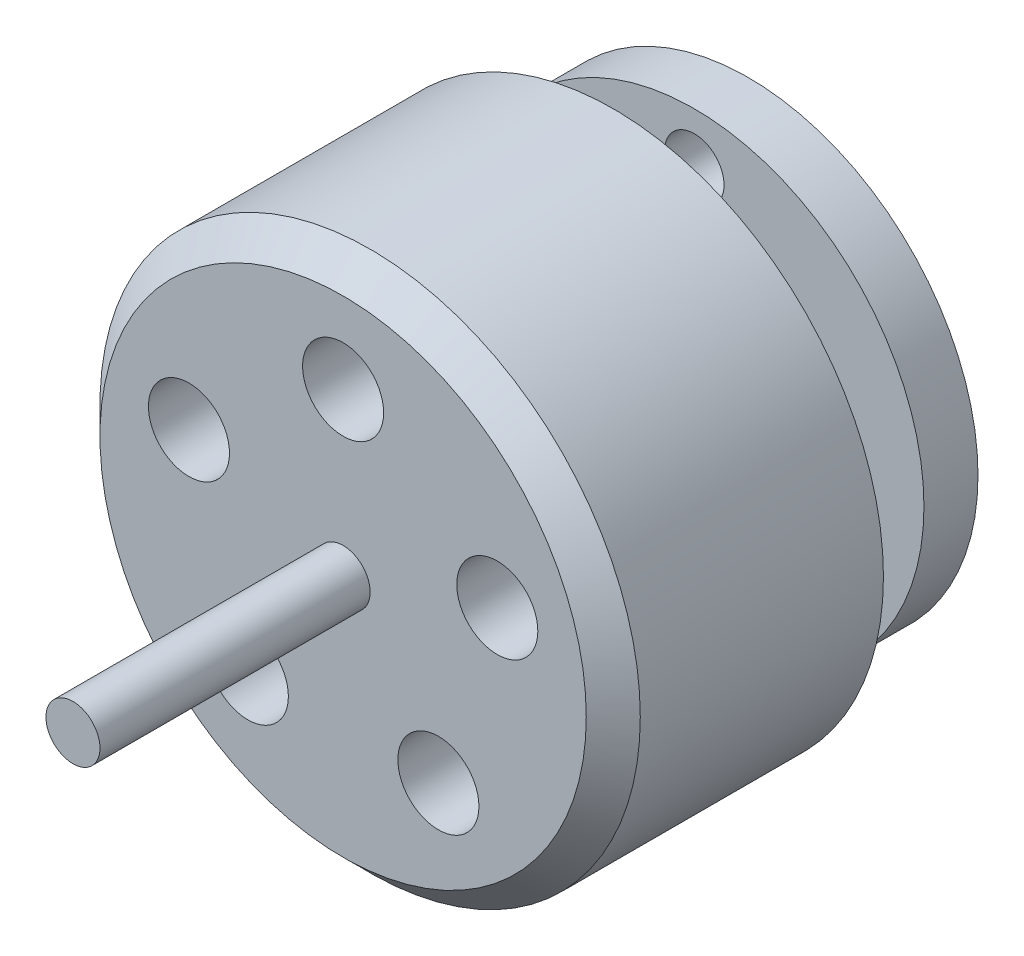
SolidWorks part; units mm, degrees
other "BLDC"
ref_plane "Front" through (0, 0, 0) normal (0, 0, 1) x (1, 0, 0)
ref_plane "Top" through (0, 0, 0) normal (0, 1, 0) x (1, 0, 0)
ref_plane "Right" through (0, 0, 0) normal (1, 0, 0) x (0, 0, -1)
sketch "Sketch1" plane through (0, 0, 0) normal (0, 0, 1) x (1, 0, 0)
  circle A0 centre (0, 0) radius 4.25
  circle A2 centre (0, 0) radius 3.3 construction
  circle A3 centre (0, 3.3) radius 0.55
  circle A4 centre (2.8579, -1.65) radius 0.55
  circle A5 centre (-2.8579, -1.65) radius 0.55
  point P13 (0, 0)
  dimension "D1" = 8.5
  dimension "D2" = 6.6
  dimension "D3" = 1.1
  dimension "D4" = 3
extrude "Boss-Extrude1" add sketch "Sketch1" along normal blind 1
sketch "Sketch2" plane through (0, 0, 1) normal (0, 0, 1) x (1, 0, 0)
  circle A0 centre (0, 0) radius 1.5
  dimension "D1" = 3
extrude "Boss-Extrude2" add sketch "Sketch2" along normal blind 1.5
sketch "Sketch3" plane through (0, 0, 2.5) normal (0, 0, 1) x (1, 0, 0)
  circle A0 centre (0, 0) radius 5
  dimension "D1" = 10
extrude "Boss-Extrude3" add sketch "Sketch3" along normal blind 5
sketch "Sketch4" plane through (0, 0, 7.5) normal (0, 0, 1) x (1, 0, 0)
  circle A0 centre (0, 0) radius 0.5
  dimension "D1" = 1
extrude "Boss-Extrude4" add sketch "Sketch4" along normal blind 5
sketch "Sketch5" plane through (0, 0, 7.5) normal (0, 0, 1) x (1, 0, 0)
  circle A0 centre (0, 3) radius 0.75
  circle A1 centre (2.8532, 0.9271) radius 0.75
  circle A2 centre (1.7634, -2.4271) radius 0.75
  circle A3 centre (-1.7634, -2.4271) radius 0.75
  circle A4 centre (-2.8532, 0.9271) radius 0.75
  point P2 (0, 0)
  point P4 (0, 0)
  point P5 (0, 0)
  point P14 (0, 0)
  point P15 (0, 0)
  point P16 (0, 0)
  dimension "D1" = 1.5
  dimension "D2" = 3
  dimension "D3" = 5
extrude "Cut-Extrude1" cut sketch "Sketch5" against normal blind 2
chamfer "Chamfer1" distance 0.5 angle 45 1 edges at (5, 0, 7.5)
